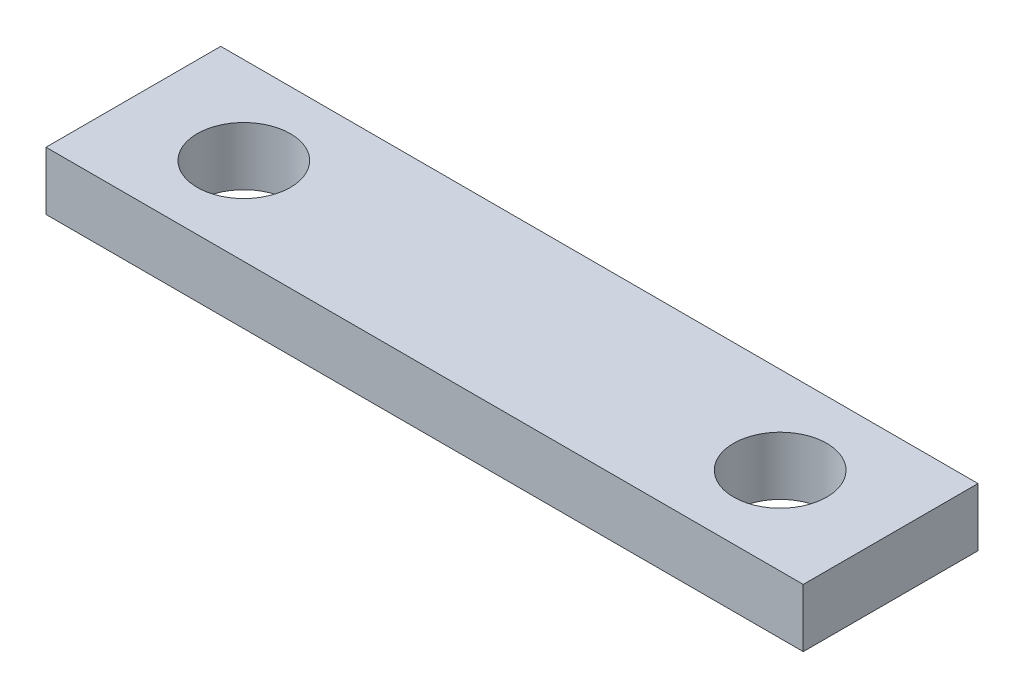
SolidWorks part; units mm, degrees
ref_plane "Front Plane" through (0, 0, 0) normal (0, 0, 1) x (1, 0, 0)
ref_plane "Top Plane" through (0, 0, 0) normal (0, 1, 0) x (1, 0, 0)
ref_plane "Right Plane" through (0, 0, 0) normal (1, 0, 0) x (0, 0, -1)
sketch "Sketch1" plane through (0, 0, 0) normal (0, 1, 0) x (1, 0, 0)
  line L0 (0, 7.5) -> (0, -7.5) construction
  line L1 (-32.5, -7.5) -> (32.5, -7.5)
  line L2 (-32.5, -7.5) -> (-32.5, 7.5)
  line L3 (-32.5, 7.5) -> (32.5, 7.5)
  line L4 (32.5, -7.5) -> (32.5, 7.5)
  line L5 (-32.5, -7.5) -> (32.5, 7.5) construction
  line L6 (-32.5, 7.5) -> (32.5, -7.5) construction
  line L7 (32.5, 0) -> (-32.5, 0) construction
  circle A0 centre (23.02, 0) radius 4
  circle A1 centre (-23.02, 0) radius 4
  point P0 (0, 0)
  dimension "D4" = 8
  dimension "D1" = 65
  dimension "D2" = 15
  dimension "D3" = 46.04
extrude "Boss-Extrude1" add sketch "Sketch1" along normal blind 5
